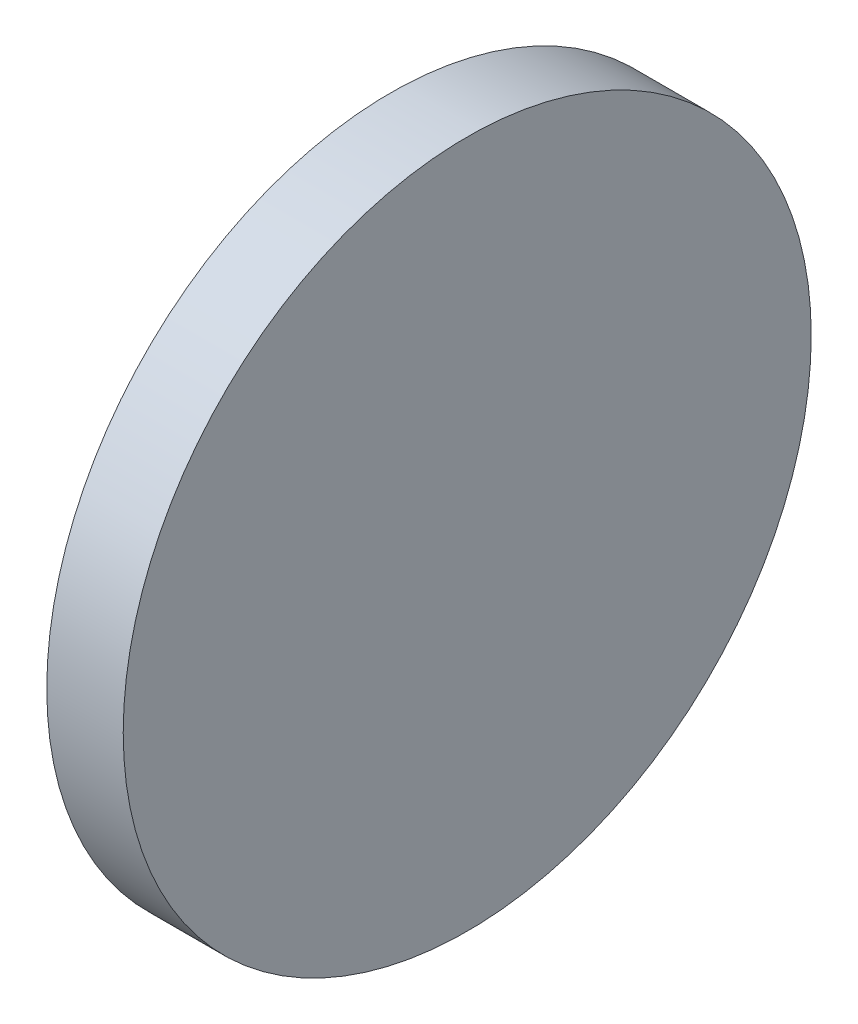
SolidWorks part; units mm, degrees
ref_plane "Front Plane" through (0, 0, 0) normal (0, 0, 1) x (1, 0, 0)
ref_plane "Top Plane" through (0, 0, 0) normal (0, 1, 0) x (1, 0, 0)
ref_plane "Right Plane" through (0, 0, 0) normal (1, 0, 0) x (0, 0, -1)
sketch "Sketch1" plane through (0, 0, 0) normal (1, 0, 0) x (0, 0, -1)
  circle A0 centre (0, 0) radius 22.5
  dimension "D1" = 45
extrude "Boss-Extrude1" add sketch "Sketch1" along normal blind 5
